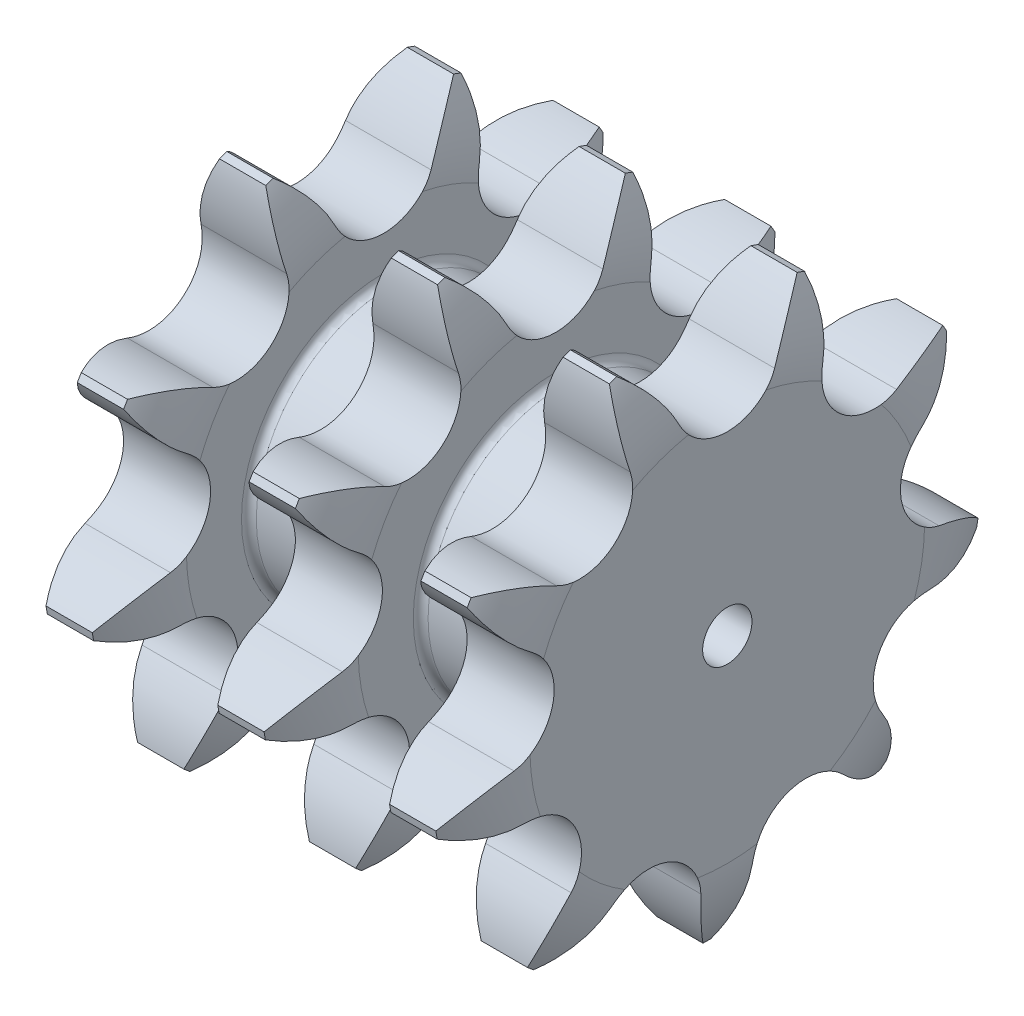
SolidWorks part; units mm, degrees
ref_plane "Plane1" through (0, 0, 0) normal (0, 0, 1) x (1, 0, 0)
ref_plane "Plane2" through (0, 0, 0) normal (0, 1, 0) x (1, 0, 0)
ref_plane "Plane3" through (0, 0, 0) normal (1, 0, 0) x (0, 0, -1)
sketch "Clipboard" plane through (0, 0, 0) normal (0, 1, 0) x (1, 0, 0)
  line L0 (0, 0) -> (12.5436, -1.9867)
  line L1 (-15, 0) -> (100, 0) construction
  line L2 (0, 0) -> (-1.094, 1.2365)
  line L3 (0, 0) -> (-11.863, 4.5341)
  line L4 (0, 0) -> (3.0618, 0.4849)
  line L5 (0, 0) -> (-46.8476, -17.4728)
  line L6 (0, 0) -> (-28.9246, -19.5155)
  line L7 (-1.094, 1.2365) -> (47.8138, 11.6322)
  line L8 (-76.2, 38.1) -> (-75.5, 38.1)
  line L9 (-73.4168, 41.5867) -> (-72.8213, 41.6603)
  line L10 (-73.7265, 13.0465) -> (-59.8065, 13.0465)
  circle A0 centre (0, 0) radius 4.255
  circle A1 centre (0, 0) radius 10.8662
  circle A2 centre (0, 0) radius 37.5
  dimension "Dr" = 8.51
  dimension "MHD" = 21.7325
  dimension "Hub_dia" = 75
  dimension "Num_teeth" = 9
  dimension "Pitch" = 12.7
  dimension "Width" = 3.1
  dimension "Side_relief" = 1.651
  dimension "Side_radius" = 12.7
  dimension "Overall_len" = 50
  dimension "Show_teeth" = 9
  dimension "Thickness" = 34.8925
  dimension "OAL" = 50.0005
  dimension "T_dim" = 0.7
  dimension "Fillet_rad" = 0.6
  dimension "Face_width" = 7.053
  dimension "Num_strands" = 3
  dimension "Transv_pitch" = 13.92
  dimension "Plate_wid" = 11.81
sketch "BasProSke" plane through (0, 0, 0) normal (0, 1, 0) x (1, 0, 0)
  line L0 (-10, 0) -> (60, 0) construction
  line L1 (0, 0) -> (0, 15.9869)
  line L2 (0, 0) -> (34.8925, 0)
  line L3 (34.8925, 0) -> (34.8925, 15.9869)
  line L4 (33.2415, 22.2487) -> (1.651, 22.2487)
  arc A0 (0, 15.9869) -> (1.651, 22.2487) centre (12.7, 15.9869) cw
  arc A1 (34.8925, 15.9869) -> (33.2415, 22.2487) centre (22.1925, 15.9869) ccw
  dimension "Thickness" = 34.8925
  dimension "D1" = 12.7
  dimension "G1" = 1.651
  dimension "G2" = 1.651
  dimension "Diameter" = 44.4973
revolve "Base-Revolve" add sketch "BasProSke" angle 360 about L0
sketch "GrvSke" plane through (0, 0, 0) normal (0, 1, 0) x (1, 0, 0)
  line L0 (7.0525, 15.9869) -> (7.0525, 11.5253)
  line L1 (7.6525, 10.9253) -> (13.32, 10.9253)
  line L2 (13.92, 11.5253) -> (13.92, 15.9869)
  line L3 (5.4015, 22.2487) -> (15.571, 22.2487)
  line L4 (10.4863, 0) -> (10.4862, 52.07) construction
  line L5 (-10, 0) -> (60, 0) construction
  line L6 (0, 0) -> (35.56, 0) construction
  arc A0 (13.92, 15.9869) -> (15.571, 22.2487) centre (26.62, 15.9869) cw
  arc A1 (7.0525, 15.9869) -> (5.4015, 22.2487) centre (-5.6475, 15.9869) ccw
  arc A2 (7.0525, 11.5253) -> (7.6525, 10.9253) centre (7.6525, 11.5253) ccw
  arc A3 (13.32, 10.9253) -> (13.92, 11.5253) centre (13.32, 11.5253) ccw
  dimension "Fillet_rad" = 0.6
  dimension "D1" = 12.7
  dimension "G1" = 1.651
  dimension "Diameter" = 44.4973
  dimension "Grv_diam" = 21.8506
  dimension "Offset" = 10.4863
  dimension "Grv_width" = 6.8675
revolve "Groove" cut sketch "GrvSke" angle 360 about L6
pattern_linear "Grooves" count 2 spacing 13.92 along (1, 0, 0) of "Groove"
sketch "TooCutSke" plane through (0, 0, 0) normal (1, 0, 0) x (0, 0, -1)
  line L0 (0, 18.6087) -> (3.8949, 16.7925) construction
  line L1 (0, 0) -> (0, 107) construction
  line L2 (0, 18.6087) -> (-10, 18.6087) construction
  line L3 (0, 18.6087) -> (-3.8949, 16.7925) construction
  arc A0 (3.8949, 16.7925) -> (7.8075, 21.3669) centre (14.0756, 12.0451) cw
  arc A1 (3.8949, 16.7925) -> (-3.8949, 16.7925) centre (0, 18.6087) cw
  arc A2 (-3.8949, 16.7925) -> (-7.8075, 21.3669) centre (-14.0756, 12.0451) ccw
  arc A3 (7.8075, 21.3669) -> (-7.8075, 21.3669) centre (0, 0) ccw
  dimension "R1" = 4.2976
  dimension "R2" = 11.2332
  dimension "Overcut" = 22.7487
  dimension "Seat_radius" = 18.6087
  dimension "X" = 130
extrude "ToothCut" cut sketch "TooCutSke" along normal through all
pattern_circular "TeethCuts" count 9 every 40 about axis through (-10, 0, 0) along (1, 0, 0) of "ToothCut"
sketch "HubNeaOneSke" plane through (0, 0, 0) normal (-1, 0, 0) x (0, 0, 1)
  circle A0 centre (0, 0) radius 10.8662
  dimension "Diameter" = 21.7325
extrude "HubNearOne" [suppressed] add sketch "HubNeaOneSke" along normal blind 15.108
fillet "HubNearOneFillet" [suppressed] radius 0.6
sketch "HubNeaBotSke" plane through (0, 0, 0) normal (-1, 0, 0) x (0, 0, 1)
  circle A0 centre (0, 0) radius 10.8662
  dimension "Diameter" = 21.7325
extrude "HubNearBoth" [suppressed] add sketch "HubNeaBotSke" along normal blind 7.554
fillet "HubNearBothFillet" [suppressed] radius 0.6
ref_plane "FarPln" through (34.8925, 0, 0) normal (1, 0, 0) x (0, 0, -1)
sketch "HubFarSke" plane through (34.8925, 0, 0) normal (1, 0, 0) x (0, 0, -1)
  circle A0 centre (0, 0) radius 10.8662
  dimension "Diameter" = 21.7325
extrude "HubFar" [suppressed] add sketch "HubFarSke" along normal blind 7.554
fillet "HubFarFillet" [suppressed] radius 0.6
sketch "BorSke" plane through (0, 0, 0) normal (1, 0, 0) x (0, 0, -1)
  circle A0 centre (0, 0) radius 2
  dimension "Diameter" = 4
extrude "Bore" cut sketch "BorSke" along normal mid plane 100.001
sketch "KeySke" plane through (0, 0, 0) normal (1, 0, 0) x (0, 0, -1)
  line L0 (-0.8, 0) -> (-0.8, 2.7)
  line L1 (-0.8, 2.7) -> (0.8, 2.7)
  line L2 (0.8, 2.7) -> (0.8, 0)
  line L3 (0, 0) -> (0, 34) construction
  line L4 (-0.8, 0) -> (0.8, 0)
  dimension "Offset" = 2.7
  dimension "Width" = 1.6
extrude "Keyway" [suppressed] cut sketch "KeySke" along normal mid plane 100.001
pattern_circular "Keyway2" [suppressed] count 2 every 90 about axis through (-10, 0, 0) along (1, 0, 0)
equation "' \"Pitch@Clipboard\" = 12.7"
equation "' \"Num_strands@Clipboard\" = 3"
equation "' \"Num_teeth@Clipboard\" = 9"
equation "' \"Hub_dia@Clipboard\" = 50"
equation "' \"Overall_len@Clipboard\" = 3"
equation "' \"Diameter@BorSke\" = 12"
equation "' \"T_dim@Clipboard\" = 1"
equation "' \"Width@KeySke\" = 2"
equation "' \"Dr@Clipboard\" = 8.51"
equation "' \"Face_width@Clipboard\" = 7.2"
equation "' \"Side_radius@Clipboard\" = 12.7"
equation "' \"Side_relief@Clipboard\" = 1.27"
equation "' \"Transv_pitch@Clipboard\" = 13.92"
equation "' \"Show_teeth@Clipboard\" = 9"
equation "' \"Fillet_rad@Clipboard\" = 0.6"
equation "' \"Plate_wid@Clipboard\" = 11.8"
equation "\"Num_teeth@Clipboard\" = int( \"Num_teeth@Clipboard\" )"
equation "\"Num_teeth@Clipboard\" = ((sgn( \"Num_teeth@Clipboard\" - 5.0)+1)*( \"Num_teeth@Clipboard\" - 5.0))/2 +5.0"
equation "\"Num_teeth@Clipboard\" = ((sgn( \"Num_teeth@Clipboard\" - 200.0)-1)*( \"Num_teeth@Clipboard\" - 200.0))/-2 +200.0"
equation "\"MHD@Clipboard\" = \"Pitch@Clipboard\" * (1.0 / tan(3.14159265 / \"Num_teeth@Clipboard\" )) - 1.05 * \"Plate_wid@Clipboard\" - 0.76"
equation "\"Thickness@Clipboard\"  = \"Face_width@Clipboard\" + (\"Num_strands@Clipboard\" - 1) * \"Transv_pitch@Clipboard\""
equation "\"OAL@Clipboard\" = \"Thickness@Clipboard\" + 2 * \"Fillet_rad@Clipboard\" + 1"
equation "\"MHD@Clipboard\" = ((sgn( \"MHD@Clipboard\" - \"Hub_dia@Clipboard\" )-1)*( \"MHD@Clipboard\" - \"Hub_dia@Clipboard\" ))/-2+ \"Hub_dia@Clipboard\""
equation "\"OAL@Clipboard\" = ((sgn( \"OAL@Clipboard\" - \"Overall_len@Clipboard\" )+1)*( \"OAL@Clipboard\" - \"Overall_len@Clipboard\" ))/2 + \"Overall_len@Clipboard\" + 0.0005"
equation "\"Num_teeth@TeethCuts\" = int( \"Show_teeth@Clipboard\" ) + 1"
equation "\"Num_teeth@TeethCuts\" = ((sgn( \"Num_teeth@TeethCuts\" - \"Num_teeth@Clipboard\" )-1)*( \"Num_teeth@TeethCuts\" - \"Num_teeth@Clipboard\" ))/-2+ \"Num_teeth@Clipboard\""
equation "\"Num_teeth@TeethCuts\" = ((sgn( \"Num_teeth@TeethCuts\" - 2.0)+1)*( \"Num_teeth@TeethCuts\" - 2.0))/2 +2.0"
equation "\"Angle@TeethCuts\" = 360.0 / \"Num_teeth@Clipboard\""
equation "\"Seat_radius@TooCutSke\" = ( \"Pitch@Clipboard\" / 2.0) / sin(3.14159265 / \"Num_teeth@Clipboard\" ) - \"Dr@Clipboard\" / 2.0 + \"Dr@Clipboard\" * 0.505"
equation "\"R1@TooCutSke\"  = \"Dr@Clipboard\" * 0.505"
equation "\"X@TooCutSke\" = 140.0 - (90.0 / \"Num_teeth@Clipboard\")"
equation "\"R2@TooCutSke\" = 0.12 * \"Dr@Clipboard\" * ( \"Num_teeth@Clipboard\" + 2.0)"
equation "\"Overcut@TooCutSke\" = 0.5 + 0.625 * \"Pitch@Clipboard\" - 0.5 * \"Dr@Clipboard\"  +  \"Pitch@Clipboard\" / 2.0 / sin(3.14159265 / \"Num_teeth@Clipboard\" )"
equation "\"Diameter@BasProSke\" = 2.0 * ( 0.625 * \"Pitch@Clipboard\" - 0.5 * \"Dr@Clipboard\"  +  \"Pitch@Clipboard\" / 2.0 / sin(3.14159265 / \"Num_teeth@Clipboard\" ))"
equation "\"Thickness@BasProSke\"  = \"Thickness@Clipboard\""
equation "\"G1@BasProSke\" =  \"Side_relief@Clipboard\""
equation "\"G2@BasProSke\" =  \"Side_relief@Clipboard\""
equation "\"D1@BasProSke\" =  \"Side_radius@Clipboard\""
equation "\"Diameter@GrvSke\" = \"Diameter@BasProSke\""
equation "\"G1@GrvSke\" = \"Side_relief@Clipboard\""
equation "\"D1@GrvSke\" = \"Side_radius@Clipboard\""
equation "\"Grv_diam@GrvSke\" =  \"Pitch@Clipboard\" * (1.0 / tan(3.14159265 / \"Num_teeth@Clipboard\" ))- 1.04 * \"Plate_wid@Clipboard\" - 0.76"
equation "\"Grv_width@GrvSke\" =  \"Transv_pitch@Clipboard\" - \"Face_width@Clipboard\""
equation "\"Offset@GrvSke\" = \"Grv_width@GrvSke\" / 2.0 + \"Face_width@Clipboard\""
equation "\"Fillet_rad@GrvSke\" = \"Fillet_rad@Clipboard\""
equation "\"Offset@Grooves\" = \"Transv_pitch@Clipboard\""
equation "\"Num_grvs@Grooves\" = \"Num_strands@Clipboard\""
equation "\"Num_grvs@Grooves\" = \"Num_grvs@Grooves\" - 1 * sgn( \"Num_grvs@Grooves\" -1)"
equation "\"Diameter@HubNeaOneSke\" = \"MHD@Clipboard\""
equation "\"Length@HubNearOne\" = \"OAL@Clipboard\" - \"Thickness@BasProSke\""
equation "\"Diameter@HubNeaBotSke\" = \"MHD@Clipboard\""
equation "\"Length@HubNearBoth\" = ( \"OAL@Clipboard\" - \"Thickness@BasProSke\" ) / 2.0"
equation "\"D1@HubNearOneFillet\" = \"Fillet_rad@Clipboard\""
equation "\"D1@HubNearBothFillet\" = \"Fillet_rad@Clipboard\""
equation "\"Thickness@FarPln\" = \"Thickness@BasProSke\""
equation "\"Diameter@HubFarSke\" = \"MHD@Clipboard\""
equation "\"Length@HubFar\" = ( \"OAL@Clipboard\" - \"Thickness@BasProSke\" ) / 2.0"
equation "\"D1@HubFarFillet\" = \"Fillet_rad@Clipboard\""
equation "\"D1@Bore\" = \"OAL@Clipboard\" * 2.0"
equation "\"D1@Keyway\" = \"OAL@Clipboard\" * 2.0"
equation "\"Offset@KeySke\" = \"T_dim@Clipboard\" + \"Diameter@BorSke\" / 2.0"
